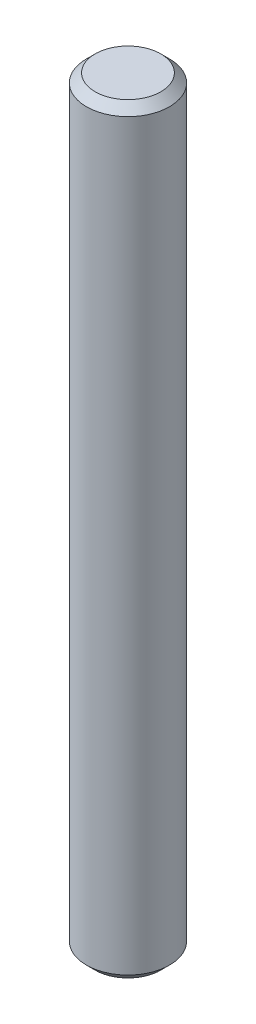
SolidWorks part; units mm, degrees
material "AISI 1020 Steel, Cold Rolled"
ref_plane "Front Plane" through (0, 0, 0) normal (0, 0, 1) x (1, 0, 0)
ref_plane "Top Plane" through (0, 0, 0) normal (0, 1, 0) x (1, 0, 0)
ref_plane "Right Plane" through (0, 0, 0) normal (1, 0, 0) x (0, 0, -1)
sketch "Sketch1" plane through (0, 0, 0) normal (0, 1, 0) x (1, 0, 0)
  circle A0 centre (0, 0) radius 1.2
  dimension "D1" = 2.4
extrude "Boss-Extrude1" add sketch "Sketch1" along normal mid plane 22
chamfer "Chamfer1" distance 0.25 angle 45 2 edges at (0, -11, 1.2) (0, 11, 1.2)
